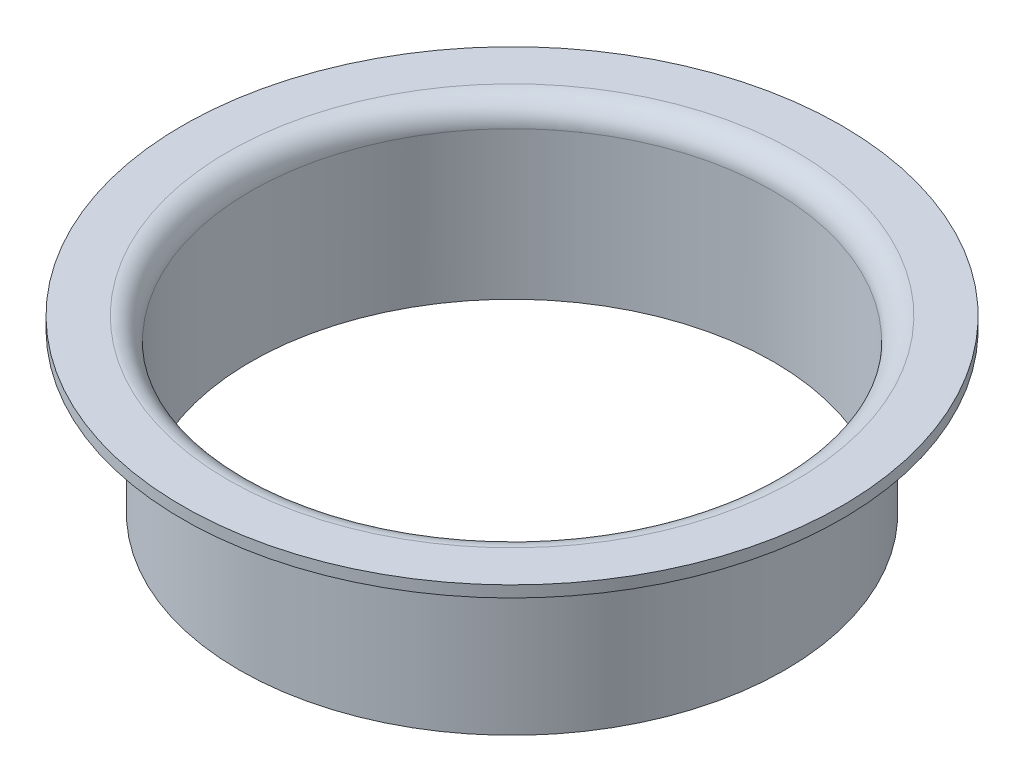
SolidWorks part; units mm, degrees
ref_plane "Front Plane" through (0, 0, 0) normal (0, 0, 1) x (1, 0, 0)
ref_plane "Top Plane" through (0, 0, 0) normal (0, 1, 0) x (1, 0, 0)
ref_plane "Right Plane" through (0, 0, 0) normal (1, 0, 0) x (0, 0, -1)
sketch "Sketch1" plane through (0, 0, 0) normal (0, 0, 1) x (1, 0, 0)
  line L0 (29.21, 0) -> (29.21, 19.05)
  line L1 (29.21, 19.05) -> (36.83, 19.05)
  line L2 (0, 0) -> (30.48, 0) construction
  line L3 (36.83, 19.05) -> (36.83, 17.78)
  line L4 (36.83, 17.78) -> (30.48, 17.78)
  line L5 (30.48, 17.78) -> (30.48, 0)
  line L6 (29.21, 0) -> (30.48, 0)
  line L7 (0, 0) -> (0, 9.0042) construction
  dimension "D1" = 1.27
  dimension "D4" = 1.27
  dimension "D5" = 6.35
  dimension "D2" = 30.48
  dimension "D3" = 19.05
revolve "Revolve1" add sketch "Sketch1" angle 360 about L7
fillet "Fillet1" radius 2.54 1 edges at (0, 19.05, -29.21)
